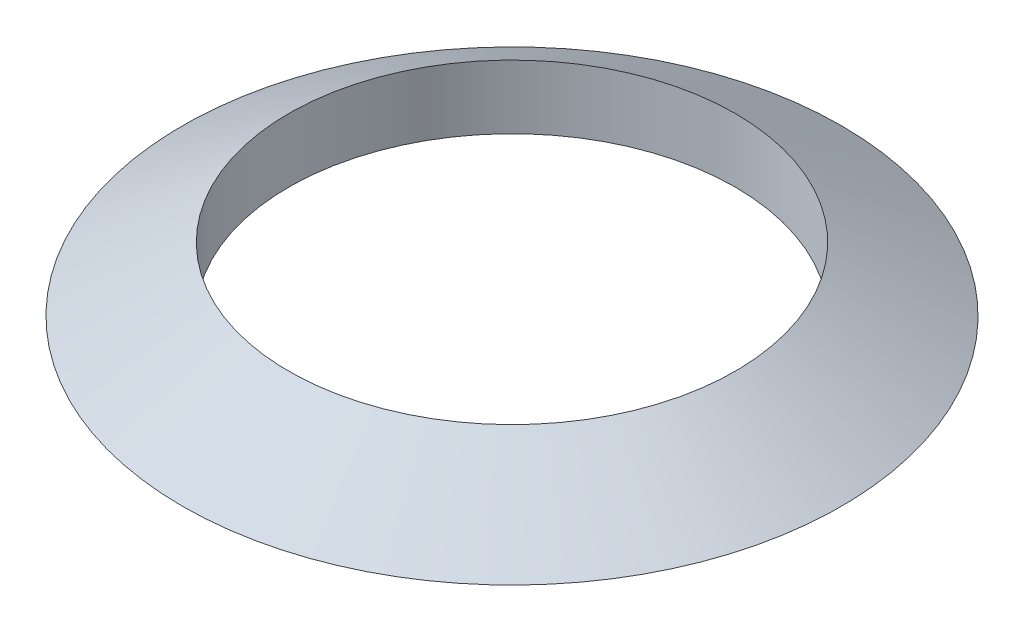
SolidWorks part; units mm, degrees
ref_plane "前视基准面" through (0, 0, 0) normal (0, 0, 1) x (1, 0, 0)
ref_plane "上视基准面" through (0, 0, 0) normal (0, 1, 0) x (1, 0, 0)
ref_plane "右视基准面" through (0, 0, 0) normal (1, 0, 0) x (0, 0, -1)
other "Configuration Table"
sketch "草图2" plane through (0, 0, 0) normal (0, 0, 1) x (1, 0, 0)
  line L0 (-155, 0) -> (-105, 0)
  line L1 (-105, 0) -> (0, 0) construction
  line L2 (-105, 0) -> (-105, 30)
  line L3 (-155, 0) -> (-105, 30)
  line L4 (0, 0) -> (0, 42.9942) construction
  dimension "D1" = 50
  dimension "D2" = 105
  dimension "D3" = 30
  dimension "D4" = 30.964
revolve "旋转1" add sketch "草图2" angle 360 about L4
sketch "草图3" plane through (0, 0, 0) normal (0, 1, 0) x (1, 0, 0)
  line L0 (0, 155) -> (-134.2339, -77.5) construction
  line L1 (-134.2339, -77.5) -> (134.2339, -77.5) construction
  line L2 (134.2339, -77.5) -> (0, 155) construction
  circle A0 centre (0, 0) radius 105
  circle A1 centre (0, 0) radius 155
  dimension "D1" = 310
